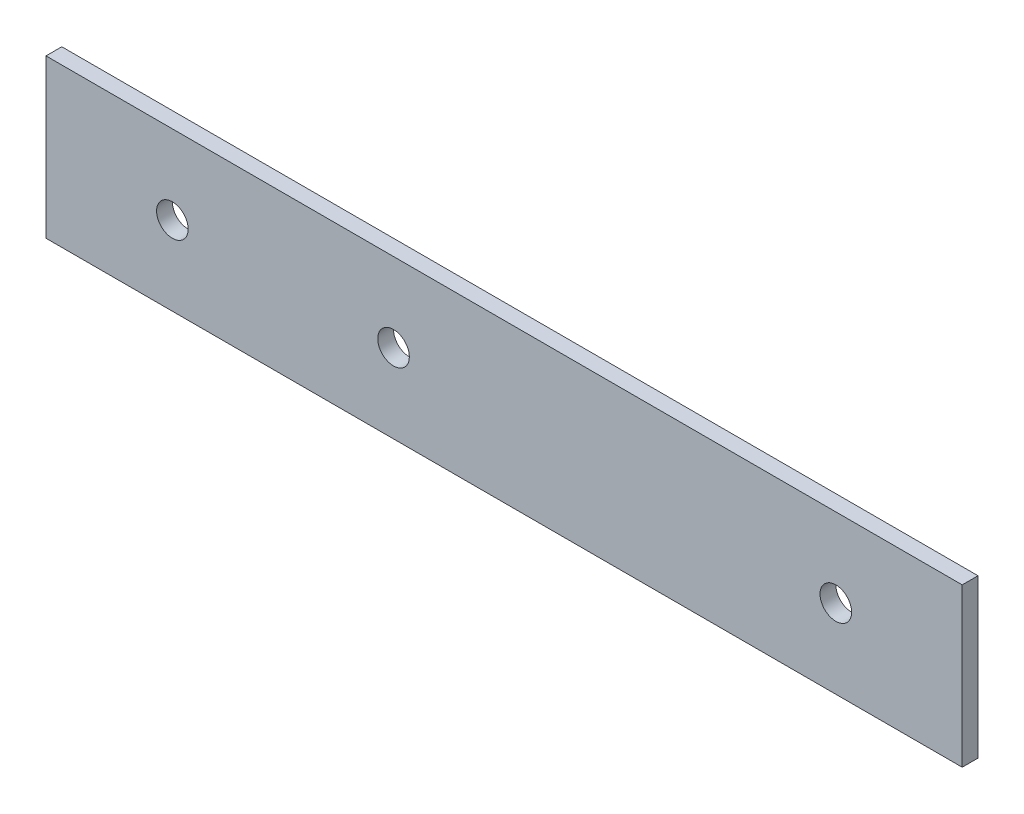
SolidWorks part; units mm, degrees
material "Galvanized Steel"
ref_plane "Front Plane" through (0, 0, 0) normal (0, 0, 1) x (1, 0, 0)
ref_plane "Top Plane" through (0, 0, 0) normal (0, 1, 0) x (1, 0, 0)
ref_plane "Right Plane" through (0, 0, 0) normal (1, 0, 0) x (0, 0, -1)
sketch "Sketch1" plane through (0, 0, 0) normal (0, 0, 1) x (1, 0, 0)
  line L1 (-123.6765, 58.3732) -> (166.3235, 58.3732)
  line L2 (-123.6765, 58.3732) -> (-123.6765, 8.3732)
  line L3 (-123.6765, 8.3732) -> (166.3235, 8.3732)
  line L4 (166.3235, 58.3732) -> (166.3235, 8.3732)
  circle A0 centre (126.3235, 33.3732) radius 5
  circle A1 centre (-13.6765, 33.3732) radius 5
  circle A2 centre (-83.6765, 33.3732) radius 5
  dimension "D3" = 210
  dimension "D4" = 70
  dimension "D5" = 25
  dimension "D6" = 10
  dimension "D7" = 10
  dimension "D8" = 10
  dimension "D9" = 40
  dimension "D1" = 290
  dimension "D2" = 50
extrude "Boss-Extrude1" add sketch "Sketch1" along normal blind 5
